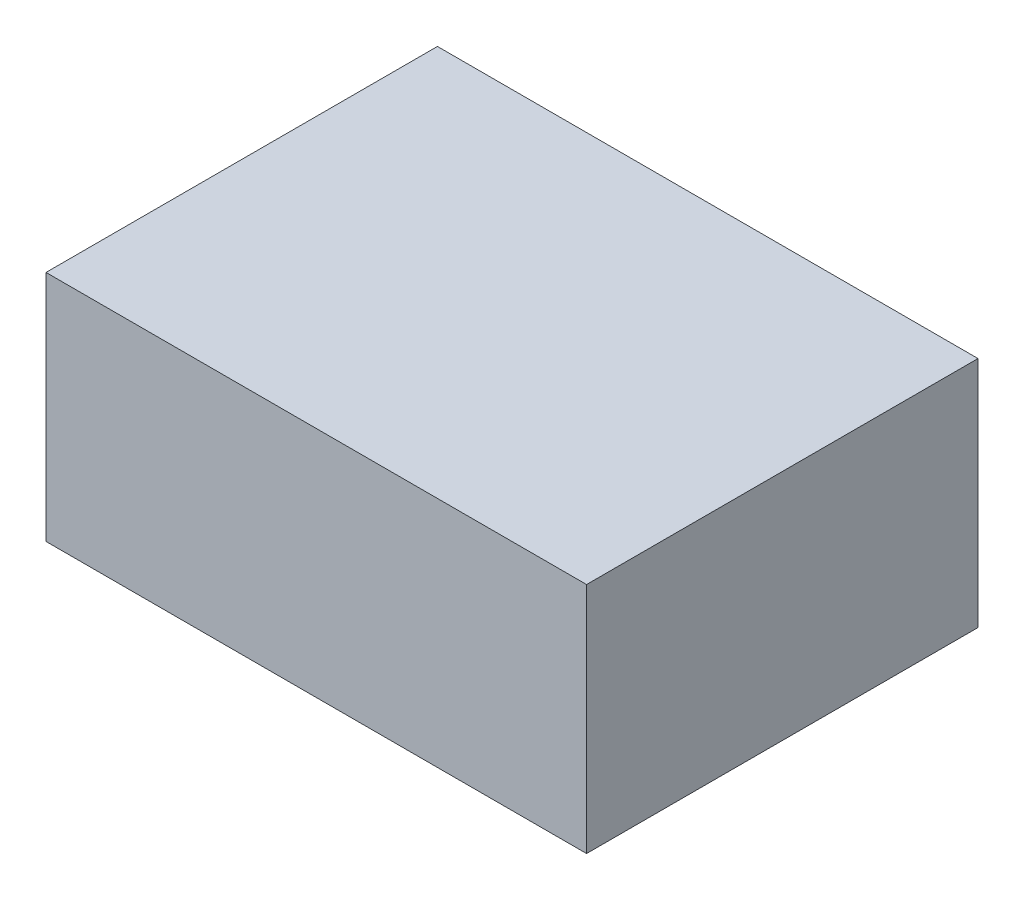
SolidWorks part; units mm, degrees
ref_plane "Front Plane" through (0, 0, 0) normal (0, 0, 1) x (1, 0, 0)
ref_plane "Top Plane" through (0, 0, 0) normal (0, 1, 0) x (1, 0, 0)
ref_plane "Right Plane" through (0, 0, 0) normal (1, 0, 0) x (0, 0, -1)
sketch "Sketch1" plane through (0, 0, 0) normal (0, 0, 1) x (1, 0, 0)
  line L1 (0, 0) -> (29, 0)
  line L2 (0, 0) -> (0, 12.5)
  line L3 (0, 12.5) -> (29, 12.5)
  line L4 (29, 0) -> (29, 12.5)
  dimension "D1" = 12.5
  dimension "D2" = 29
extrude "Boss-Extrude1" add sketch "Sketch1" along normal blind 21
